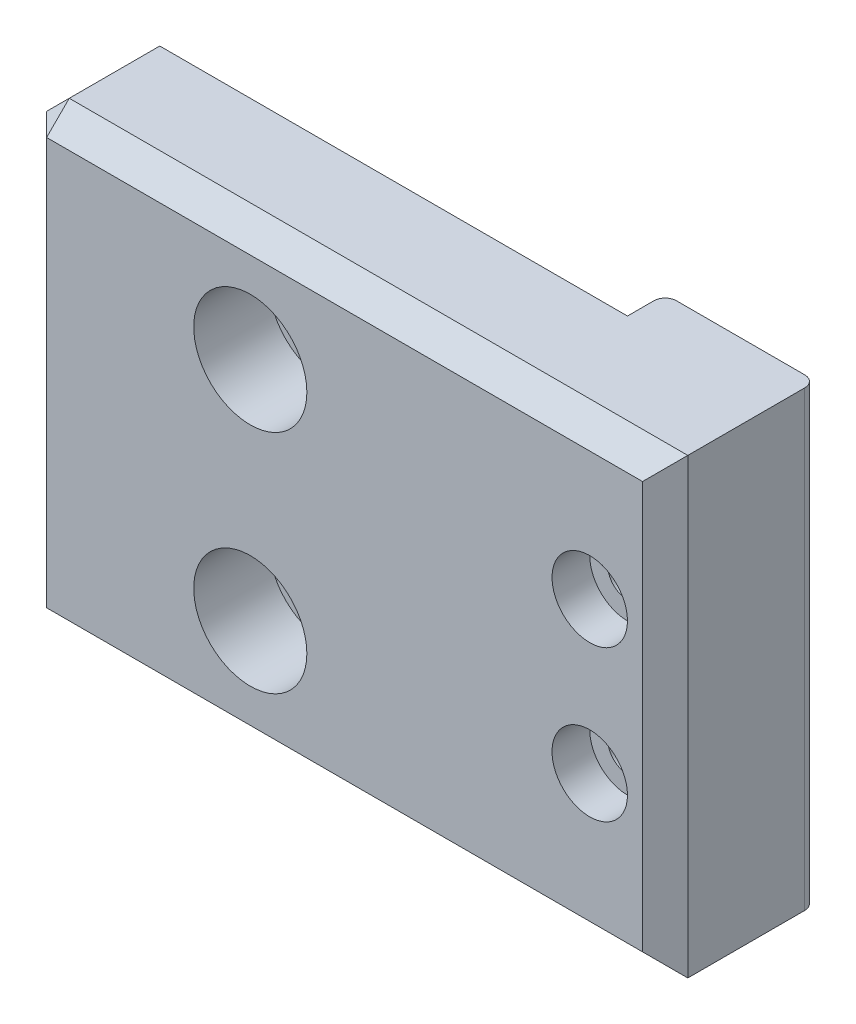
SolidWorks part; units mm, degrees
ref_plane "Płaszczyzna przednia" through (0, 0, 0) normal (0, 0, 1) x (1, 0, 0)
ref_plane "Płaszczyzna górna" through (0, 0, 0) normal (0, 1, 0) x (1, 0, 0)
ref_plane "Płaszczyzna prawa" through (0, 0, 0) normal (1, 0, 0) x (0, 0, -1)
sketch "Sketch1" plane through (0, 0, 0) normal (0, 0, 1) x (1, 0, 0)
  line L0 (0, 0) -> (0, 60)
  line L1 (0, 60) -> (-85, 60)
  line L2 (-85, 60) -> (-85, 0)
  line L3 (-85, 0) -> (0, 0)
  dimension "D2" = 60
  dimension "D3" = 85
  dimension "D4" = 60
extrude "Boss-Extrude1" add sketch "Sketch1" along normal blind 15
sketch "Sketch2" plane through (0, 0, 0) normal (0, 0, 1) x (1, 0, 0)
  line L0 (0, 60) -> (-85, 60) construction
  line L1 (-20, 60) -> (0, 60)
  line L2 (-20, 60) -> (-20, 0)
  line L3 (-20, 0) -> (0, 0)
  line L4 (0, 60) -> (0, 0)
  line L7 (-85, 0) -> (0, 0) construction
  line L8 (0, 0) -> (0, 60) construction
  dimension "D1" = 20
extrude "Boss-Extrude2" add sketch "Sketch2" against normal blind 5
sketch "Sketch3" plane through (0, 0, 0) normal (0, 0, 1) x (1, 0, 0)
  line L0 (-10, 60) -> (-10, 0) construction
  line L1 (0, 60) -> (-85, 60) construction
  line L5 (0, 0) -> (0, 60) construction
  circle A0 centre (-10, 40) radius 2.6
  circle A1 centre (-10, 20) radius 2.6
  dimension "D4" = 5.2
  dimension "D5" = 5.2
  dimension "D1" = 10
  dimension "D2" = 20
  dimension "D3" = 20
extrude "Cut-Extrude1" cut sketch "Sketch3" against normal through all both and the other way through all
sketch "Sketch4" plane through (0, 0, 0) normal (0, 0, 1) x (1, 0, 0)
  circle A0 centre (-10, 40) radius 5
  circle A1 centre (-10, 20) radius 5
  dimension "D1" = 10
  dimension "D2" = 10
extrude "Cut-Extrude2" cut sketch "Sketch4" against normal blind 5 from surface at 15 starting at face at (-7.4, 40, 15)
fillet "Fillet1" radius 1.5 2 edges at (-20, 30, -5) (0, 30, -5)
sketch "Sketch5" plane through (0, 0, 0) normal (0, 0, 1) x (1, 0, 0)
  line L0 (-55, 60) -> (-55, 0) construction
  line L1 (0, 60) -> (-85, 60) construction
  line L2 (-85, 0) -> (0, 0) construction
  line L3 (-85, 60) -> (-85, 0) construction
  circle A0 centre (-55, 45) radius 4.1
  circle A1 centre (-55, 15) radius 4.1
  dimension "D2" = 15
  dimension "D4" = 8.2
  dimension "D1" = 30
  dimension "D3" = 15
extrude "Cut-Extrude3" cut sketch "Sketch5" against normal through all both and the other way through all
sketch "Sketch6" plane through (0, 0, 0) normal (0, 0, 1) x (1, 0, 0)
  circle A0 centre (-55, 45) radius 7.5
  circle A1 centre (-55, 15) radius 7.5
  dimension "D1" = 15
  dimension "D2" = 15
extrude "Cut-Extrude4" cut sketch "Sketch6" against normal blind 10 from surface at 15 starting at face at (-50.9, 45, 15)
chamfer "Chamfer1" distance 3 angle 45 8 edges at (0, 0, 5.75) (0, 60, 5.75) (-85, 60, 7.5) (-85, 0, 7.5) (-85, 30, 15) (-42.5, 0, 15) (0, 30, 15) (-42.5, 60, 15)
